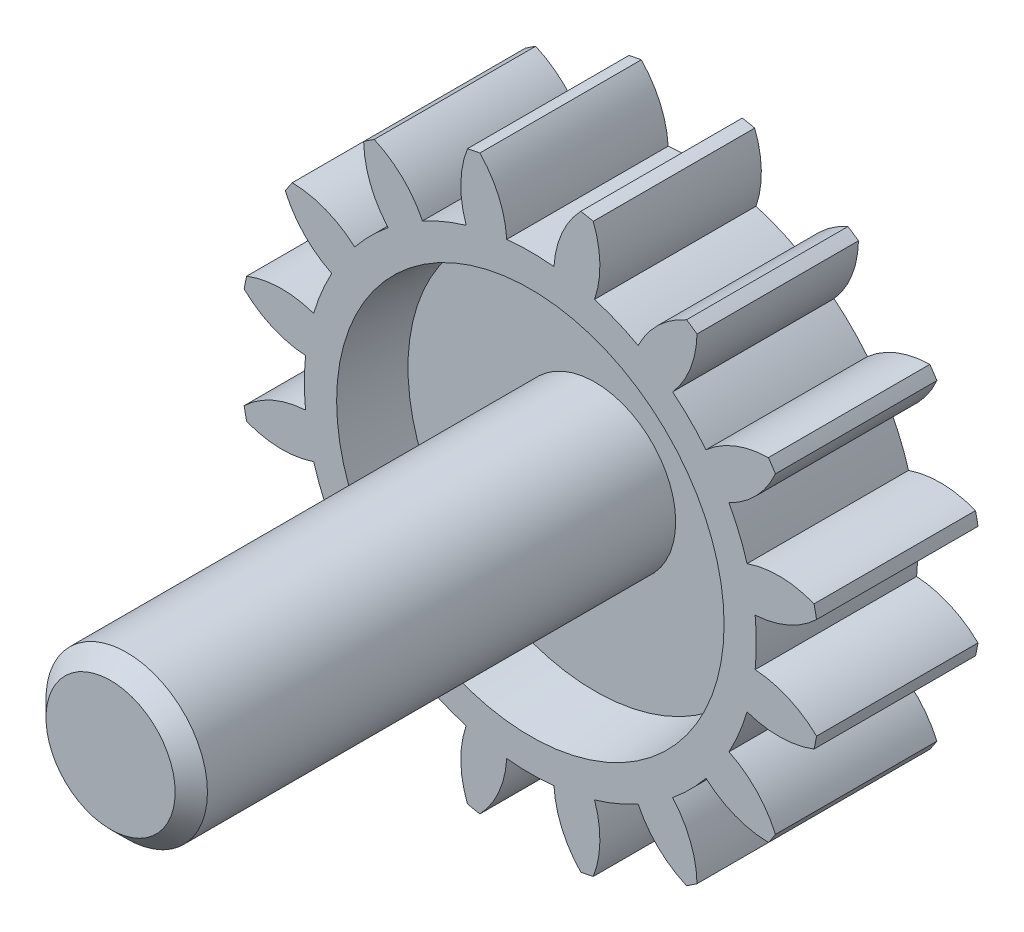
SolidWorks part; units mm, degrees
ref_plane "Спереди" through (0, 0, 0) normal (0, 0, 1) x (1, 0, 0)
ref_plane "Сверху" through (0, 0, 0) normal (0, 1, 0) x (1, 0, 0)
ref_plane "Справа" through (0, 0, 0) normal (1, 0, 0) x (0, 0, -1)
sketch "Эскиз1" plane through (0, 0, 0) normal (0, 0, 1) x (1, 0, 0)
  circle A0 centre (0, 0) radius 18
  dimension "D1" = 36
extrude "Бобышка-Вытянуть1" add sketch "Эскиз1" against normal blind 10
sketch "Эскиз5" plane through (0, 0, 0) normal (0, 0, 1) x (1, 0, 0)
  line L0 (0, 0) -> (0, 19.8392) construction
  line L1 (0, 0) -> (-2.093, 19.9134) construction
  line L2 (0, 0) -> (-3.5908, 20.3642) construction
  arc A0 (1.4634, 13.9233) -> (-1.4634, 13.9233) centre (0, 0) ccw
  arc A1 (-1.4634, 13.9233) -> (0, 14) centre (0, 0) cw
  arc A2 (-1.4634, 13.9233) -> (-3.1257, 17.7265) centre (-7.453, 13.5703) ccw
  circle A3 centre (0, 0) radius 18 construction
  arc A4 (-3.1257, 17.7265) -> (3.1257, 17.7265) centre (0, 0) cw
  arc A5 (1.4634, 13.9233) -> (3.1257, 17.7265) centre (7.453, 13.5703) cw
  circle M7 centre (0, 0) radius 18
  dimension "D3" = 14
  dimension "D4" = 6
  dimension "D1" = 10
  dimension "D2" = 6
extrude "Вырез-Вытянуть4" cut sketch "Эскиз5" against normal blind 10 contours A0 A5 A2 M7
pattern_circular "Круговой массив1" count 16 over 360 about axis through (0, 0, 0) along (0, 0, 1) of "Вырез-Вытянуть4"
sketch "Эскиз6" plane through (0, 0, 0) normal (0, 0, 1) x (1, 0, 0)
  circle A0 centre (0, 0) radius 12
  dimension "D1" = 24
extrude "Вырез-Вытянуть5" cut sketch "Эскиз6" against normal blind 4 draft 6
sketch "Эскиз7" plane through (0, 0, -10) normal (0, 0, -1) x (-1, 0, 0)
  circle A0 centre (0, 0) radius 12
  dimension "D1" = 24
extrude "Вырез-Вытянуть6" cut sketch "Эскиз7" against normal blind 4 draft 6
sketch "Эскиз10" plane through (0, 0, -4) normal (0, 0, 1) x (1, 0, 0)
  circle A0 centre (0, 0) radius 5
  dimension "D1" = 10
extrude "Бобышка-Вытянуть2" add sketch "Эскиз10" along normal blind 30
chamfer "Фаска2" distance 1 angle 45 1 edges at (5, 0, 26)
